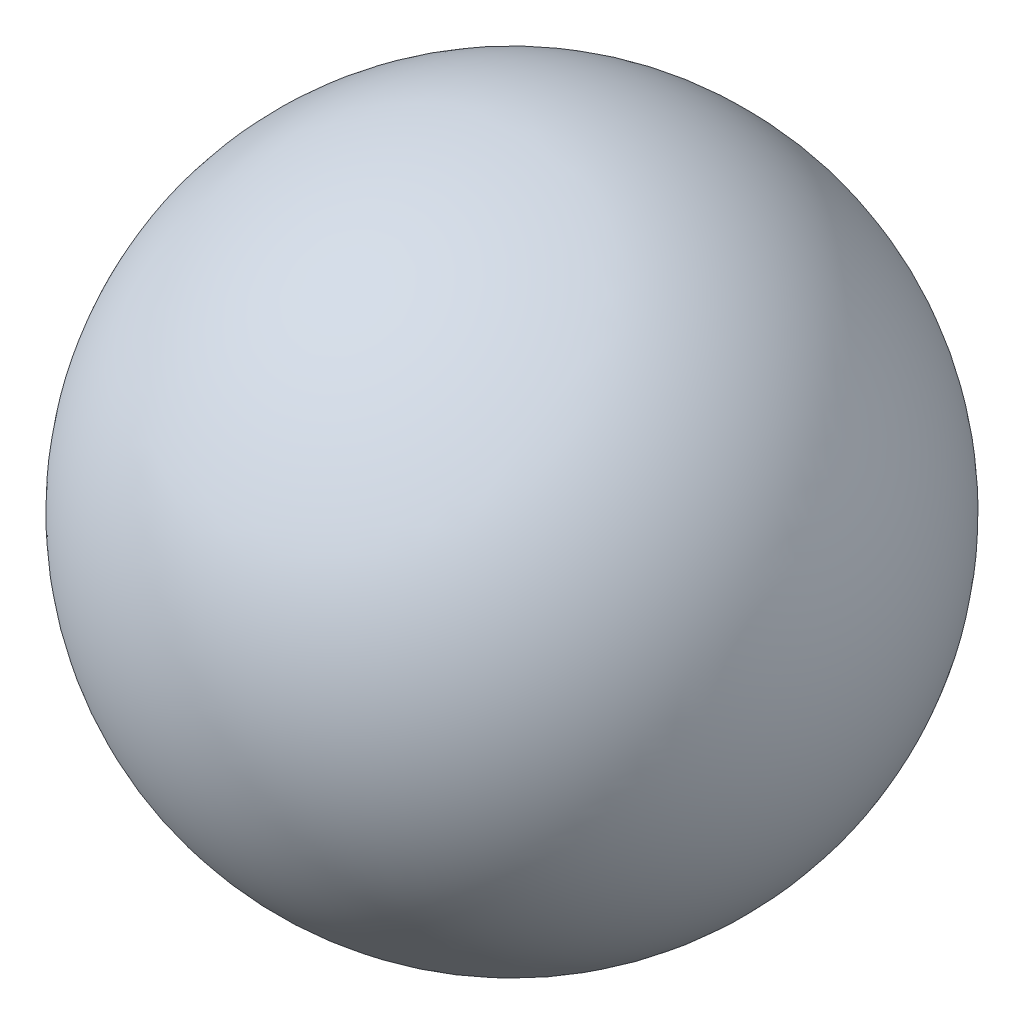
SolidWorks part; units mm, degrees
ref_plane "Plan de face" through (0, 0, 0) normal (0, 0, 1) x (1, 0, 0)
ref_plane "Plan de dessus" through (0, 0, 0) normal (0, 1, 0) x (1, 0, 0)
ref_plane "Plan de droite" through (0, 0, 0) normal (1, 0, 0) x (0, 0, -1)
sketch "Esquisse1" plane through (0, 0, 0) normal (0, 0, 1) x (1, 0, 0)
  line L0 (0, 0) -> (25.4, 0)
  arc A0 (0, 0) -> (25.4, 0) centre (12.7, 0) cw
  dimension "D1" = 12.7
revolve "Révolution1" add sketch "Esquisse1" angle 360 about L0
